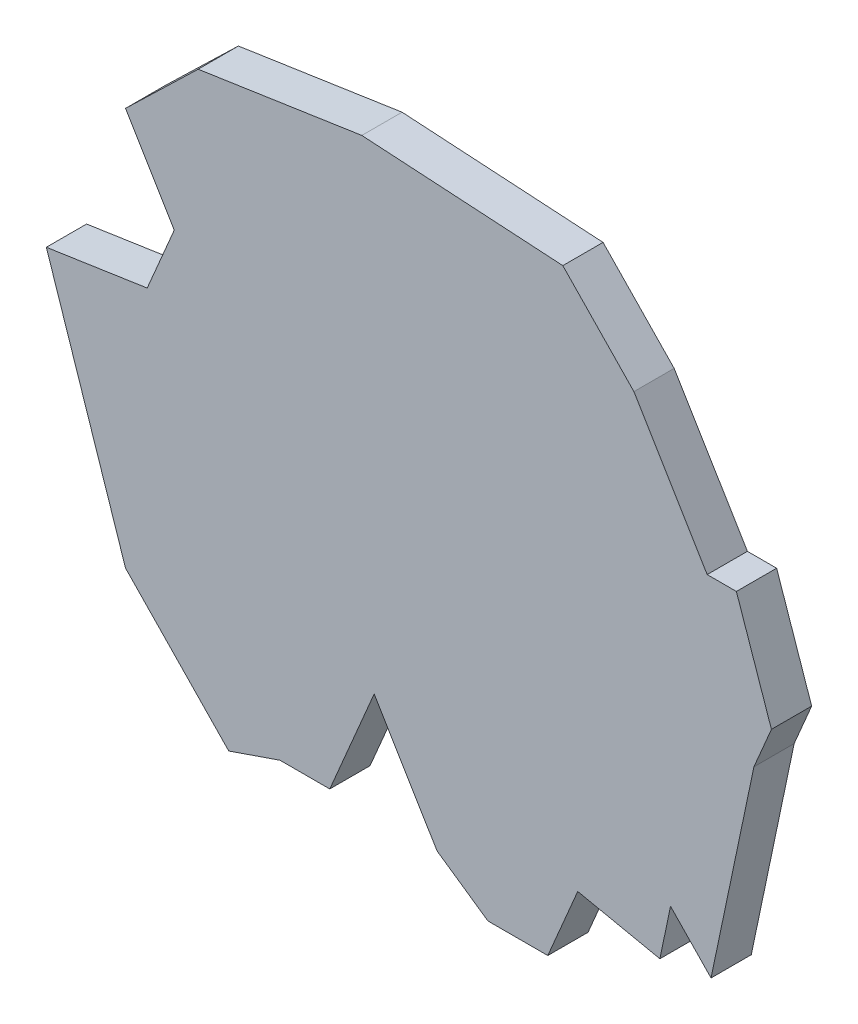
SolidWorks part; units mm, degrees
ref_plane "Спереди" through (0, 0, 0) normal (0, 0, 1) x (1, 0, 0)
ref_plane "Сверху" through (0, 0, 0) normal (0, 1, 0) x (1, 0, 0)
ref_plane "Справа" through (0, 0, 0) normal (1, 0, 0) x (0, 0, -1)
sketch "Эскиз1" plane through (0, 0, 0) normal (0, 0, 1) x (1, 0, 0)
  line L0 (159.8076, 1028.3907) -> (1311.8076, 1028.3907) construction
  line L7 (-103.9936, 0) -> (-78.9257, 3.7545)
  line L8 (-78.9257, 3.7545) -> (-72.1975, 19.5854)
  line L9 (-72.1975, 19.5854) -> (-84.3143, 39.7333)
  line L10 (-84.3143, 39.7333) -> (-66.2609, 57.1838)
  line L11 (-66.2609, 57.1838) -> (-25.5791, 63.2768)
  line L12 (-25.5791, 63.2768) -> (24.371, 60.2303)
  line L13 (24.371, 60.2303) -> (42.0377, 41.9533)
  line L14 (42.0377, 41.9533) -> (60.2498, 11.6699)
  line L15 (60.2498, 11.6699) -> (67.5102, 11.6699)
  line L16 (67.5102, 11.6699) -> (76.2172, -13.6595)
  line L17 (76.2172, -13.6595) -> (71.8637, -23.903)
  line L18 (71.8637, -23.903) -> (63.88, -61.9437)
  line L19 (63.88, -61.9437) -> (61.2056, -74.6865)
  line L20 (61.2056, -74.6865) -> (51.1437, -64.277)
  line L21 (51.1437, -64.277) -> (48.4931, -76.9069)
  line L22 (48.4931, -76.9069) -> (28.0809, -72.6229)
  line L23 (28.0809, -72.6229) -> (20.6368, -90.1386)
  line L24 (20.6368, -90.1386) -> (5.7697, -90.1386)
  line L25 (5.7697, -90.1386) -> (-6.8951, -81.3807)
  line L26 (-6.8951, -81.3807) -> (-22.5126, -55.4117)
  line L27 (-22.5126, -55.4117) -> (-33.5495, -81.3807)
  line L28 (-33.5495, -81.3807) -> (-45.92, -81.3807)
  line L29 (-45.92, -81.3807) -> (-58.6587, -85.7597)
  line L30 (-58.6587, -85.7597) -> (-84.3143, -59.2177)
  line L31 (-84.3143, -59.2177) -> (-103.9936, 0)
extrude "Бобышка-Вытянуть1" add sketch "Эскиз1" along normal blind 10 contours L31 L7 L8 L9 L10 L11 L12 L13 L14 L15 L16 L17 L18 L19 L20 L21 L22 L23 L24 L25 L26 L27 L28 L29 L30
